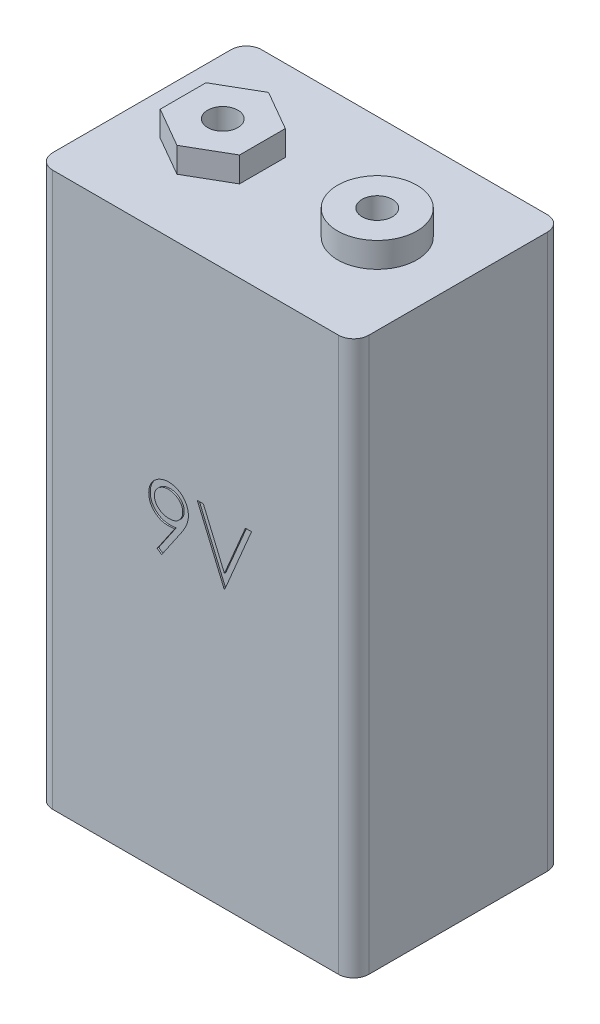
SolidWorks part; units mm, degrees
ref_plane "Front Plane" through (0, 0, 0) normal (0, 0, 1) x (1, 0, 0)
ref_plane "Top Plane" through (0, 0, 0) normal (0, 1, 0) x (1, 0, 0)
ref_plane "Right Plane" through (0, 0, 0) normal (1, 0, 0) x (0, 0, -1)
sketch "Sketch1" plane through (0, 0, 0) normal (0, 0, 1) x (1, 0, 0)
  line L1 (-13.25, 23.2) -> (13.25, 23.2)
  line L2 (-13.25, 23.2) -> (-13.25, -23.2)
  line L3 (-13.25, -23.2) -> (13.25, -23.2)
  line L4 (13.25, 23.2) -> (13.25, -23.2)
  line L5 (-13.25, 23.2) -> (13.25, -23.2) construction
  line L6 (-13.25, -23.2) -> (13.25, 23.2) construction
  point P0 (0, 0)
  dimension "D1" = 46.4
  dimension "D2" = 26.5
extrude "Boss-Extrude1" add sketch "Sketch1" along normal mid plane 17.5
sketch "Sketch2" plane through (0, 23.2, 0) normal (0, 1, 0) x (1, 0, 0)
  line L0 (-6.475, 3.8394) -> (-9.8, 1.9197)
  line L1 (-9.8, 1.9197) -> (-9.8, -1.9197)
  line L2 (-9.8, -1.9197) -> (-6.475, -3.8394)
  line L3 (-6.475, -3.8394) -> (-3.15, -1.9197)
  line L4 (-3.15, -1.9197) -> (-3.15, 1.9197)
  line L5 (-3.15, 1.9197) -> (-6.475, 3.8394)
  line L6 (-6.475, 3.8394) -> (-6.475, -3.8394) construction
  circle A0 centre (6.475, 0) radius 3.325
  circle A1 centre (6.475, 0) radius 1.27
  circle A2 centre (-6.475, 0) radius 1.27
  point P5 (-6.475, 0)
  point P12 (6.3703, -1.6434)
  point P13 (0, 0)
  dimension "D5" = 6.65
  dimension "D6" = 2.54
  dimension "D1" = 120
  dimension "D2" = 6.65
  dimension "D3" = 6.475
  dimension "D4" = 12.95
extrude "Boss-Extrude2" add sketch "Sketch2" along normal blind 2.1
sketch "Sketch3" plane through (0, 0, 8.75) normal (0, 0, 1) x (1, 0, 0)
  line L0 (-4.2, 0) -> (3.7495, 0) construction
  text T0 "9V" font "Century Gothic" height in points 20
  point P4 (-4.5725, 0)
  point P5 (0, 0)
  point P6 (-3.1551, 0)
  point P7 (0, 0)
  point P8 (-1.9662, 0)
  point P9 (0, 0)
  point P10 (0, 0)
  point P11 (0, 0)
  point P12 (-2.1948, 0)
  point P13 (0, 0)
  point P14 (3.7495, 0)
  point P15 (-3.8867, 0)
  point P16 (0, 0)
  point P17 (0, 0)
  point P18 (0, 0)
  point P19 (-4.2, 0)
extrude "Cut-Extrude1" cut sketch "Sketch3" against normal blind 0.127
fillet "Fillet1" radius 1.27 4 edges at (13.25, 0, -8.75) (13.25, 0, 8.75) (-13.25, 0, -8.75) (-13.25, 0, 8.75)
